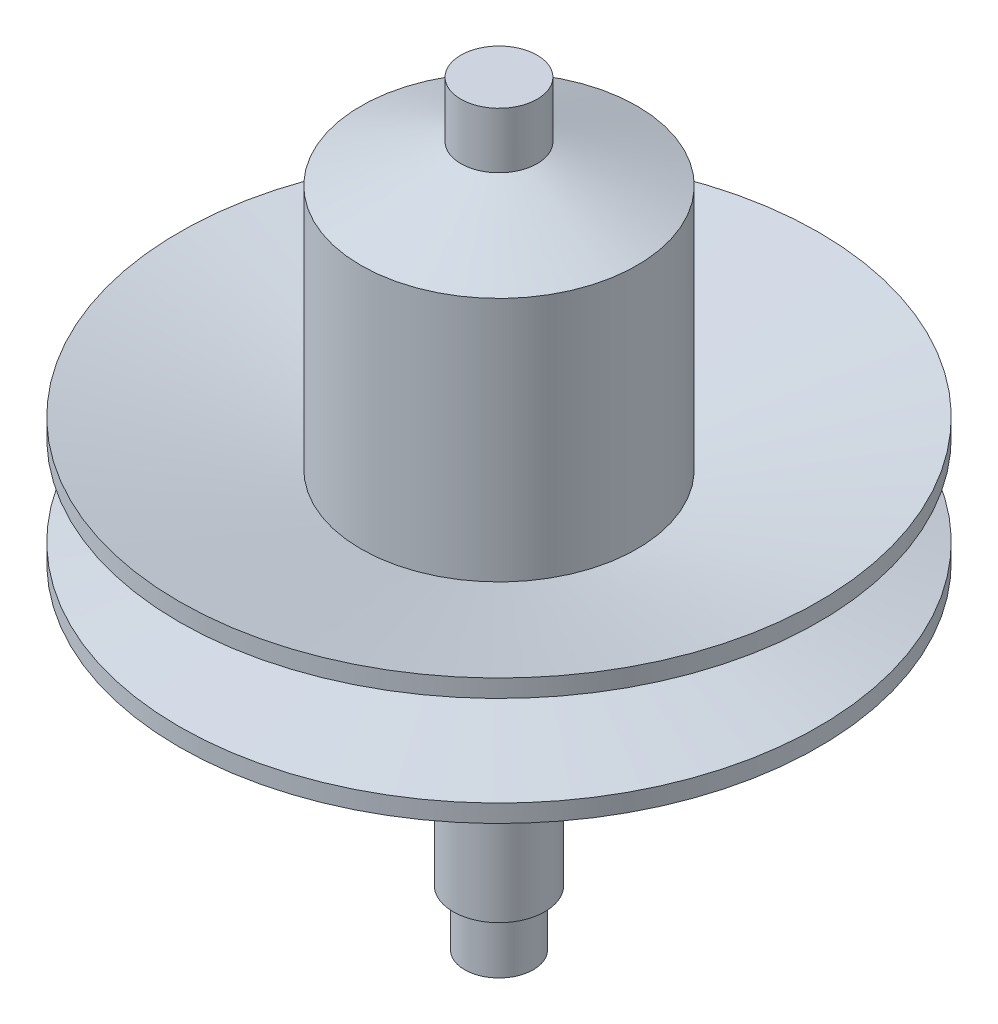
SolidWorks part; units mm, degrees
material "Plain Carbon Steel"
ref_plane "Front Plane" through (0, 0, 0) normal (0, 0, 1) x (1, 0, 0)
ref_plane "Top Plane" through (0, 0, 0) normal (0, 1, 0) x (1, 0, 0)
ref_plane "Right Plane" through (0, 0, 0) normal (1, 0, 0) x (0, 0, -1)
sketch "Sketch1" plane through (0, 0, 0) normal (0, 0, 1) x (1, 0, 0)
  line L0 (0, 0) -> (0, 111.0296) construction
  line L1 (0, 111.0296) -> (0, 0) construction
  line L2 (0, 99.06) -> (5, 99.06)
  line L3 (5, 99.06) -> (5, 91.74)
  line L4 (5, 91.74) -> (18.0975, 86.74)
  line L5 (41.91, 43.988) -> (18.0975, 49.9241)
  line L6 (41.91, 43.988) -> (41.91, 46.3069)
  line L7 (41.91, 46.3069) -> (18.0975, 52.243)
  line L8 (18.0975, 86.74) -> (18.0975, 54.5619)
  line L9 (6, 7.3358) -> (6, 49.9241)
  line L10 (6, 49.9241) -> (18.0975, 49.9241)
  line L11 (18.0975, 52.243) -> (41.91, 58.1791)
  line L12 (41.91, 58.1791) -> (41.91, 60.498)
  line L13 (41.91, 60.498) -> (18.0975, 54.5619)
  line L14 (0, 99.06) -> (0, 0)
  line L16 (6, 7.3358) -> (4.5, 7.3358)
  line L17 (4.5, 7.3358) -> (4.5, 0)
  line L18 (4.5, 0) -> (0, 0)
  dimension "D1" = 4.5
  dimension "D2" = 84.4042
  dimension "D3" = 6
  dimension "D4" = 5
  dimension "D5" = 5
  dimension "D6" = 18.0975
  dimension "D7" = 7.32
  dimension "D8" = 41.91
  dimension "D9" = 99.06
  dimension "D10" = 2.25
  dimension "D11" = 16.51
  dimension "D12" = 47.752
revolve "Revolve1" add sketch "Sketch1" angle 360 about L14
